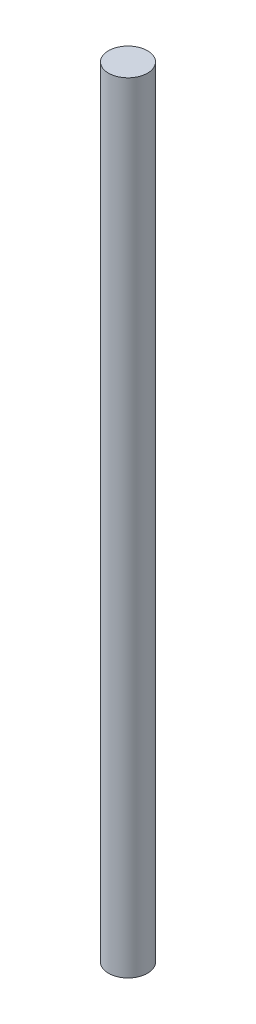
SolidWorks part; units mm, degrees
ref_plane "Front Plane" through (0, 0, 0) normal (0, 0, 1) x (1, 0, 0)
ref_plane "Top Plane" through (0, 0, 0) normal (0, 1, 0) x (1, 0, 0)
ref_plane "Right Plane" through (0, 0, 0) normal (1, 0, 0) x (0, 0, -1)
sketch "Sketch1" plane through (0, 0, 0) normal (0, 1, 0) x (1, 0, 0)
  circle A0 centre (0, 0) radius 0.8
  dimension "D1" = 1.6
extrude "Boss-Extrude1" add sketch "Sketch1" along normal blind 32
